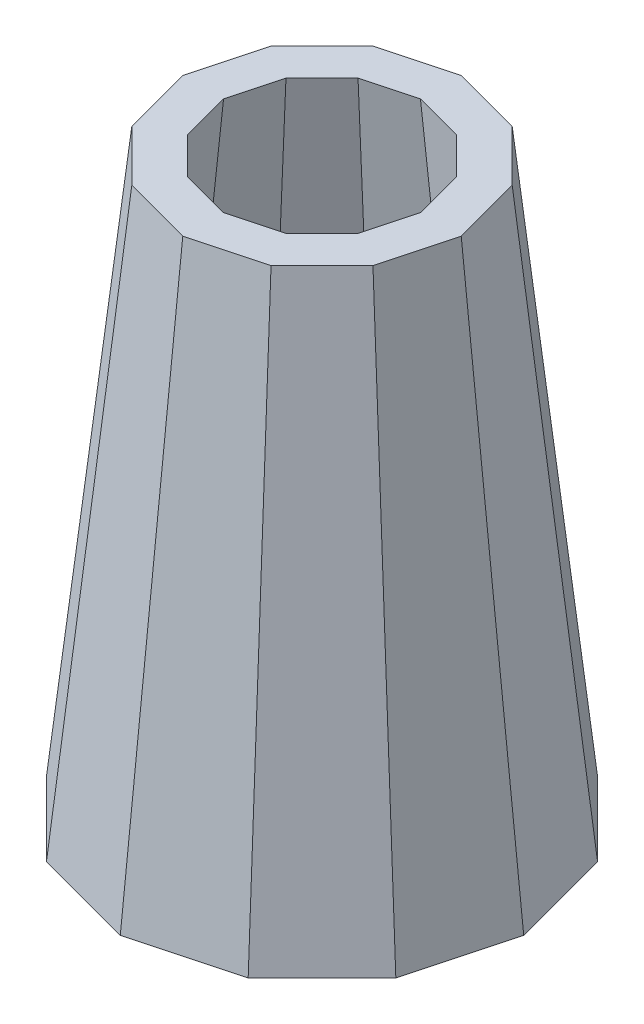
SolidWorks part; units mm, degrees
ref_plane "Front" through (0, 0, 0) normal (0, 0, 1) x (1, 0, 0)
ref_plane "Top" through (0, 0, 0) normal (0, 1, 0) x (1, 0, 0)
ref_plane "Right" through (0, 0, 0) normal (1, 0, 0) x (0, 0, -1)
sketch "Sketch1" plane through (0, 0, 0) normal (0, 1, 0) x (1, 0, 0)
  line L1 (98.1381, 0) -> (84.9901, 49.069)
  line L2 (84.9901, 49.069) -> (49.069, 84.9901)
  line L3 (49.069, 84.9901) -> (0, 98.1381)
  line L4 (0, 98.1381) -> (-49.069, 84.9901)
  line L5 (-49.069, 84.9901) -> (-84.9901, 49.069)
  line L6 (-84.9901, 49.069) -> (-98.1381, 0)
  line L7 (-98.1381, 0) -> (-84.9901, -49.069)
  line L8 (-84.9901, -49.069) -> (-49.069, -84.9901)
  line L9 (-49.069, -84.9901) -> (0, -98.1381)
  line L10 (0, -98.1381) -> (49.069, -84.9901)
  line L11 (49.069, -84.9901) -> (84.9901, -49.069)
  line L12 (84.9901, -49.069) -> (98.1381, 0)
  circle A0 centre (0, 0) radius 94.7941 construction
  dimension "D1" = 50.8
extrude "Boss-Extrude1" add sketch "Sketch1" along normal blind 279.4 draft 6
shell "Shell1" thickness 19.05
